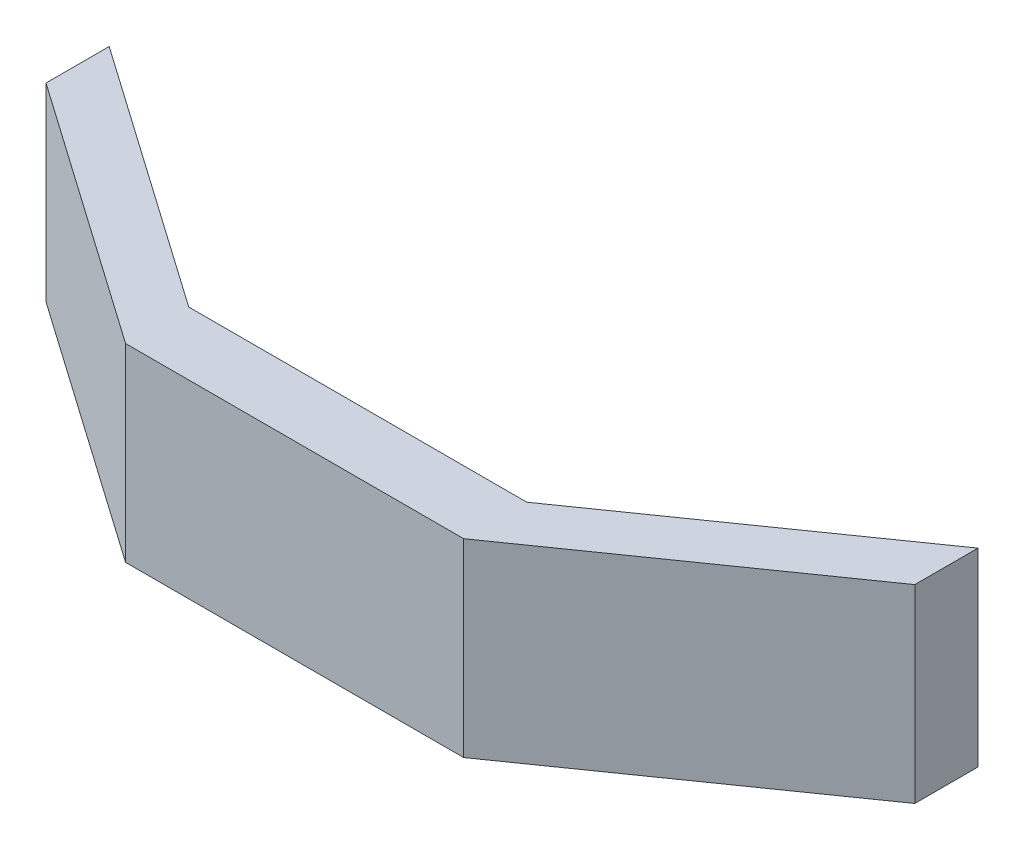
SolidWorks part; units mm, degrees
material "ABS"
ref_plane "Alzado" through (0, 0, 0) normal (0, 0, 1) x (1, 0, 0)
ref_plane "Planta" through (0, 0, 0) normal (0, 1, 0) x (1, 0, 0)
ref_plane "Vista lateral" through (0, 0, 0) normal (1, 0, 0) x (0, 0, -1)
sketch "Sketch1" plane through (0, 0, 0) normal (0, 1, 0) x (1, 0, 0)
  line L0 (-53.5, 10) -> (-137.4963, 68.8148)
  line L1 (-53.5, -10) -> (53.5, -10)
  line L2 (-53.5, -10) -> (-53.5, 10) construction
  line L3 (-53.5, 10) -> (53.5, 10)
  line L4 (53.5, -10) -> (53.5, 10) construction
  line L5 (-53.5, -10) -> (53.5, 10) construction
  line L6 (-53.5, 10) -> (53.5, -10) construction
  line L7 (-137.4963, 68.8148) -> (-137.4963, 48.8148)
  line L8 (-137.4963, 48.8148) -> (-53.5, -10)
  line L9 (0, -1856.5515) -> (0, 90971.0218) construction
  line L10 (137.4963, 48.8148) -> (53.5, -10)
  line L11 (137.4963, 68.8148) -> (137.4963, 48.8148)
  line L12 (53.5, 10) -> (137.4963, 68.8148)
  point P0 (0, 0)
  dimension "D1" = 20
  dimension "D2" = 35
  dimension "D3" = 107
  dimension "D4" = 102.5405
extrude "Boss-Extrude1" add sketch "Sketch1" along normal blind 60
